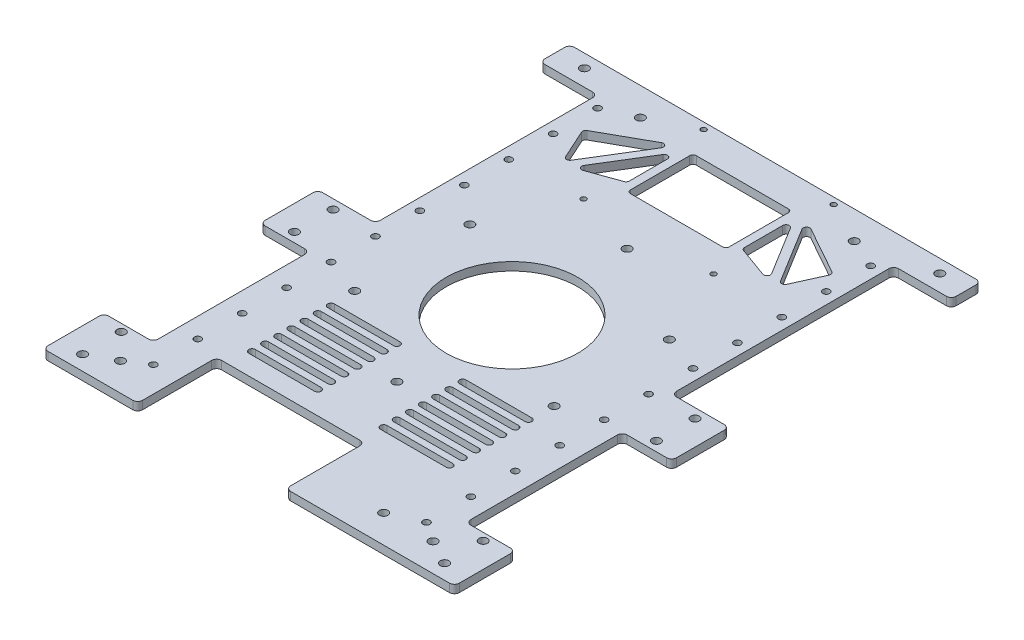
SolidWorks part; units mm, degrees
material "Thornel Mat VMA"
ref_plane "前视基准面" through (0, 0, 0) normal (0, 0, 1) x (1, 0, 0)
ref_plane "上视基准面" through (0, 0, 0) normal (0, 1, 0) x (1, 0, 0)
ref_plane "右视基准面" through (0, 0, 0) normal (1, 0, 0) x (0, 0, -1)
other "Configuration Table"
sketch "草图1" plane through (0, 0, 0) normal (0, 1, 0) x (1, 0, 0)
  line L1 (125, -160) -> (-125, -160)
  line L2 (125, -160) -> (125, 160)
  line L3 (125, 160) -> (-125, 160)
  line L4 (-125, -160) -> (-125, 160)
  line L5 (125, -160) -> (-125, 160) construction
  line L6 (125, 160) -> (-125, -160) construction
  point P0 (0, 0)
  dimension "D1" = 250
  dimension "D2" = 320
extrude "凸台-拉伸1" add sketch "草图1" along normal blind 5
sketch "草图2" plane through (0, 5, 0) normal (0, 1, 0) x (1, 0, 0)
  circle A0 centre (0, 0) radius 70 construction
  circle A1 centre (0, 70) radius 2.6
  circle A2 centre (60.6218, 35) radius 2.6
  circle A3 centre (60.6218, -35) radius 2.6
  circle A4 centre (0, -70) radius 2.6
  circle A5 centre (-60.6218, -35) radius 2.6
  circle A6 centre (-60.6218, 35) radius 2.6
  circle A7 centre (0, 0) radius 40
  point P17 (0, 0)
  dimension "D1" = 140
  dimension "D2" = 5.2
  dimension "D4" = 80
  dimension "D3" = 6
extrude "切除-拉伸1" cut sketch "草图2" against normal blind 50
sketch "草图3" plane through (0, 5, 0) normal (0, 1, 0) x (1, 0, 0)
  line L0 (-125, 160) -> (-125, -160) construction
  line L1 (-125, 142) -> (-90, 142)
  line L2 (-125, 142) -> (-125, 7)
  line L3 (-125, 7) -> (-90, 7)
  line L4 (-90, 142) -> (-90, 7)
  line L5 (-125, 0) -> (125, 0) construction
  line L6 (125, -160) -> (125, 160) construction
  line L7 (0, 160) -> (0, -160) construction
  line L8 (125, 160) -> (-125, 160) construction
  line L9 (-125, -160) -> (125, -160) construction
  line L10 (125, 7) -> (90, 7)
  line L11 (90, 142) -> (90, 7)
  line L12 (125, 142) -> (90, 142)
  line L13 (125, 142) -> (125, 7)
  line L14 (125, -123) -> (95, -123)
  line L15 (-125, -28) -> (-95, -28)
  line L16 (-125, -28) -> (-125, -123)
  line L17 (-125, -123) -> (-95, -123)
  line L18 (-95, -28) -> (-95, -123)
  line L19 (95, -28) -> (95, -123)
  line L20 (125, -28) -> (95, -28)
  line L21 (125, -28) -> (125, -123)
  dimension "D1" = 18
  dimension "D2" = 35
  dimension "D3" = 135
  dimension "D4" = 37
  dimension "D5" = 95
  dimension "D6" = 30
extrude "切除-拉伸2" cut sketch "草图3" against normal blind 50
fillet "圆角1" radius 3 20 edges at (90, 2.5, -142) (125, 2.5, -142) (125, 2.5, -160) (-125, 2.5, -160) (-90, 2.5, -142) (-90, 2.5, -7) (-125, 2.5, -7) (-125, 2.5, 28) (-95, 2.5, 28) (-95, 2.5, 123) (-125, 2.5, 123) (-125, 2.5, 160) (125, 2.5, 160) (125, 2.5, 123) (95, 2.5, 123) (95, 2.5, 28) (125, 2.5, 28) (125, 2.5, -7) (90, 2.5, -7) (-125, 2.5, -142)
sketch "草图6" plane through (0, 5, 0) normal (0, 1, 0) x (1, 0, 0)
  line L0 (-125, -10.5) -> (125, -10.5) construction
  line L1 (-125, 4) -> (-125, -25) construction
  line L2 (125, -25) -> (125, 4) construction
  line L3 (-110, 1.25) -> (-110, -22.25) construction
  line L4 (0, 160) -> (0, -160) construction
  line L5 (122, 160) -> (-122, 160) construction
  line L6 (-122, -160) -> (122, -160) construction
  line L7 (110, 1.25) -> (110, -22.25) construction
  line L8 (-110, -127.5) -> (-110, -151) construction
  line L9 (110, -127.5) -> (110, -151) construction
  circle A0 centre (-110, 1.25) radius 2.6
  circle A1 centre (-110, -22.25) radius 2.6
  circle A2 centre (110, -22.25) radius 2.6
  circle A3 centre (110, 1.25) radius 2.6
  circle A4 centre (-110, -127.5) radius 2.6
  circle A5 centre (-110, -151) radius 2.6
  circle A6 centre (110, -151) radius 2.6
  circle A7 centre (110, -127.5) radius 2.6
  dimension "D1" = 23.5
  dimension "D2" = 11.75
  dimension "D3" = 5.2
  dimension "D4" = 5.2
  dimension "D6" = 5.2
  dimension "D7" = 23.5
  dimension "D8" = 9
  dimension "D5" = 15
extrude "切除-拉伸4" cut sketch "草图6" against normal blind 100
sketch "草图7" plane through (0, 5, 0) normal (0, 1, 0) x (1, 0, 0)
  line L0 (0, 160) -> (0, -160) construction
  line L1 (122, 160) -> (-122, 160) construction
  line L2 (-122, -160) -> (122, -160) construction
  line L3 (-83, 160) -> (-83, -160) construction
  line L4 (83, 160) -> (83, -160) construction
  circle A0 centre (-83, 135) radius 2.1
  circle A1 centre (-83, 108) radius 2.1
  circle A2 centre (-83, 81) radius 2.1
  circle A3 centre (-83, 54) radius 2.1
  circle A4 centre (-83, 27) radius 2.1
  circle A5 centre (-83, 0) radius 2.1
  circle A6 centre (-83, -27) radius 2.1
  circle A7 centre (-83, -54) radius 2.1
  circle A8 centre (-83, -81) radius 2.1
  circle A9 centre (-83, -108) radius 2.1
  circle A10 centre (-83, -135) radius 2.1
  circle A11 centre (83, -135) radius 2.1
  circle A12 centre (83, -108) radius 2.1
  circle A13 centre (83, -81) radius 2.1
  circle A14 centre (83, -54) radius 2.1
  circle A15 centre (83, -27) radius 2.1
  circle A16 centre (83, 0) radius 2.1
  circle A17 centre (83, 27) radius 2.1
  circle A18 centre (83, 54) radius 2.1
  circle A19 centre (83, 81) radius 2.1
  circle A20 centre (83, 108) radius 2.1
  circle A21 centre (83, 135) radius 2.1
  dimension "D2" = 4.2
  dimension "D3" = 27
  dimension "D5" = 25
  dimension "D1" = 83
  dimension "D4" = 11
extrude "切除-拉伸5" cut sketch "草图7" against normal blind 500
sketch "草图8" plane through (0, 0, 0) normal (0, -1, 0) x (-1, 0, 0)
  line L0 (122, -160) -> (-122, -160) construction
  line L1 (-22.5, -160) -> (67.5, -160)
  line L2 (-22.5, -160) -> (-22.5, -112)
  line L3 (-22.5, -112) -> (67.5, -112)
  line L4 (67.5, -160) -> (67.5, -112)
  line L6 (125, -126) -> (125, -157) construction
  dimension "D1" = 48
  dimension "D2" = 90
  dimension "D3" = 57.5
extrude "切除-拉伸6" cut sketch "草图8" against normal blind 10
fillet "圆角2" radius 3 4 edges at (22.5, 2.5, 112) (-67.5, 2.5, 112) (22.5, 2.5, 160) (-67.5, 2.5, 160)
sketch "草图9" plane through (0, 5, 0) normal (0, 1, 0) x (1, 0, 0)
  line L0 (0, 160) -> (0, 0) construction
  line L1 (122, 160) -> (-122, 160) construction
  line L3 (39.5, 156) -> (-39.5, 156) construction
  line L4 (39.5, 156) -> (39.5, 83) construction
  line L5 (39.5, 83) -> (-39.5, 83) construction
  line L6 (-39.5, 156) -> (-39.5, 83) construction
  line L7 (39.5, 156) -> (-39.5, 83) construction
  line L8 (39.5, 83) -> (-39.5, 156) construction
  circle A0 centre (-39.5, 156) radius 1.6
  circle A1 centre (39.5, 156) radius 1.6
  circle A2 centre (39.5, 83) radius 1.6
  circle A3 centre (-39.5, 83) radius 1.6
  point P5 (0, 119.5)
  dimension "D4" = 3.2
  dimension "D1" = 79
  dimension "D2" = 73
  dimension "D3" = 4
extrude "切除-拉伸7" cut sketch "草图9" against normal blind 10
sketch "草图10" plane through (0, 5, 0) normal (0, 1, 0) x (1, 0, 0)
  line L0 (-125, 152) -> (125, 152) construction
  line L1 (-125, 157) -> (-125, 145) construction
  line L2 (125, 145) -> (125, 157) construction
  line L3 (-93, 142) -> (-122, 142) construction
  line L4 (-125, -126) -> (-125, -157) construction
  line L5 (-122, -160) -> (-70.5, -160) construction
  line L6 (0, 0) -> (0, -216.7517) construction
  circle A0 centre (-108, 152) radius 2.6
  circle A1 centre (108, 152) radius 2.6
  circle A2 centre (-95, -143) radius 2.6
  circle A3 centre (95, -143) radius 2.6
  dimension "D1" = 5.2
  dimension "D2" = 17
  dimension "D3" = 5.2
  dimension "D4" = 17
  dimension "D6" = 5.2
  dimension "D7" = 30
  dimension "D8" = 17
  dimension "D5" = 10
extrude "切除-拉伸8" cut sketch "草图10" against normal blind 10
sketch "草图12" plane through (0, 5, 0) normal (0, 1, 0) x (1, 0, 0)
  line L0 (65, 160) -> (65, -160) construction
  line L1 (122, 160) -> (-122, 160) construction
  line L2 (25.5, -160) -> (122, -160) construction
  line L3 (125, -25) -> (125, 4) construction
  line L4 (0, 160) -> (0, -112) construction
  line L5 (19.5, -112) -> (-64.5, -112) construction
  circle A0 centre (65, 143) radius 2.6
  circle A2 centre (65, -143) radius 2.6
  circle A3 centre (-65, 143) radius 2.6
  dimension "D2" = 5.2
  dimension "D3" = 17
  dimension "D4" = 17
  dimension "D1" = 60
extrude "切除-拉伸9" cut sketch "草图12" against normal blind 10
sketch "草图13" plane through (0, 5, 0) normal (0, 1, 0) x (1, 0, 0)
  line L4 (0, 160) -> (0, -112) construction
  line L5 (-30, 140) -> (30, 140)
  line L6 (-30, 140) -> (-30, 100)
  line L7 (-30, 100) -> (30, 100)
  line L8 (30, 140) -> (30, 100)
  line L9 (122, 160) -> (-122, 160) construction
  line L10 (19.5, -112) -> (-64.5, -112) construction
  line L11 (35, 136.5726) -> (35, 104.9002)
  line L12 (35, 104.9002) -> (60, 95.925)
  line L13 (60, 95.925) -> (35, 136.5726)
  line L14 (38.762, 140) -> (65.6284, 96.3179)
  line L15 (65.6284, 96.3179) -> (76, 119.1776)
  line L16 (76, 119.1776) -> (38.762, 140)
  line L17 (-65.6284, 96.3179) -> (-76, 119.1776)
  line L18 (-38.762, 140) -> (-65.6284, 96.3179)
  line L19 (-76, 119.1776) -> (-38.762, 140)
  line L20 (-35, 104.9002) -> (-60, 95.925)
  line L21 (-35, 136.5726) -> (-35, 104.9002)
  line L22 (-60, 95.925) -> (-35, 136.5726)
  line L23 (-90, 10) -> (-90, 139) construction
  line L24 (-60, -50) -> (-20, -50) construction
  line L25 (-60, -48) -> (-20, -48)
  line L26 (-60, -52) -> (-20, -52)
  line L27 (-98, -28) -> (-122, -28) construction
  line L28 (-60, -58) -> (-20, -58) construction
  line L29 (-60, -56) -> (-20, -56)
  line L30 (-60, -60) -> (-20, -60)
  line L31 (-60, -66) -> (-20, -66) construction
  line L32 (-60, -64) -> (-20, -64)
  line L33 (-60, -68) -> (-20, -68)
  line L34 (-60, -74) -> (-20, -74) construction
  line L35 (-60, -72) -> (-20, -72)
  line L36 (-60, -76) -> (-20, -76)
  line L37 (-60, -82) -> (-20, -82) construction
  line L38 (-60, -80) -> (-20, -80)
  line L39 (-60, -84) -> (-20, -84)
  line L40 (-60, -90) -> (-20, -90) construction
  line L41 (-60, -88) -> (-20, -88)
  line L42 (-60, -92) -> (-20, -92)
  line L43 (60, -90) -> (20, -90) construction
  line L44 (60, -88) -> (20, -88)
  line L45 (60, -92) -> (20, -92)
  line L46 (60, -82) -> (20, -82) construction
  line L47 (60, -80) -> (20, -80)
  line L48 (60, -84) -> (20, -84)
  line L49 (60, -74) -> (20, -74) construction
  line L50 (60, -72) -> (20, -72)
  line L51 (60, -76) -> (20, -76)
  line L52 (60, -66) -> (20, -66) construction
  line L53 (60, -64) -> (20, -64)
  line L54 (60, -68) -> (20, -68)
  line L55 (60, -58) -> (20, -58) construction
  line L56 (60, -56) -> (20, -56)
  line L57 (60, -60) -> (20, -60)
  line L58 (60, -50) -> (20, -50) construction
  line L59 (60, -48) -> (20, -48)
  line L60 (60, -52) -> (20, -52)
  line L61 (-60, -98) -> (-20, -98) construction
  line L62 (-60, -96) -> (-20, -96)
  line L63 (-60, -100) -> (-20, -100)
  line L64 (60, -98) -> (20, -98) construction
  line L67 (60, -96) -> (20, -96)
  line L68 (60, -100) -> (20, -100)
  arc A0 (-60, -48) -> (-60, -52) centre (-60, -50) ccw
  arc A1 (-20, -52) -> (-20, -48) centre (-20, -50) ccw
  arc A2 (-60, -56) -> (-60, -60) centre (-60, -58) ccw
  arc A3 (-20, -60) -> (-20, -56) centre (-20, -58) ccw
  arc A4 (-60, -64) -> (-60, -68) centre (-60, -66) ccw
  arc A5 (-20, -68) -> (-20, -64) centre (-20, -66) ccw
  arc A6 (-60, -72) -> (-60, -76) centre (-60, -74) ccw
  arc A7 (-20, -76) -> (-20, -72) centre (-20, -74) ccw
  arc A8 (-60, -80) -> (-60, -84) centre (-60, -82) ccw
  arc A9 (-20, -84) -> (-20, -80) centre (-20, -82) ccw
  arc A10 (-60, -88) -> (-60, -92) centre (-60, -90) ccw
  arc A11 (-20, -92) -> (-20, -88) centre (-20, -90) ccw
  arc A12 (60, -88) -> (60, -92) centre (60, -90) cw
  arc A13 (20, -92) -> (20, -88) centre (20, -90) cw
  arc A14 (60, -80) -> (60, -84) centre (60, -82) cw
  arc A15 (20, -84) -> (20, -80) centre (20, -82) cw
  arc A16 (60, -72) -> (60, -76) centre (60, -74) cw
  arc A17 (20, -76) -> (20, -72) centre (20, -74) cw
  arc A18 (60, -64) -> (60, -68) centre (60, -66) cw
  arc A19 (20, -68) -> (20, -64) centre (20, -66) cw
  arc A20 (60, -56) -> (60, -60) centre (60, -58) cw
  arc A21 (20, -60) -> (20, -56) centre (20, -58) cw
  arc A22 (60, -48) -> (60, -52) centre (60, -50) cw
  arc A23 (20, -52) -> (20, -48) centre (20, -50) cw
  arc A24 (-60, -96) -> (-60, -100) centre (-60, -98) ccw
  arc A25 (-20, -100) -> (-20, -96) centre (-20, -98) ccw
  arc A28 (60, -96) -> (60, -100) centre (60, -98) cw
  arc A29 (20, -100) -> (20, -96) centre (20, -98) cw
  point P27 (-40, -50)
  point P38 (-40, -58)
  point P45 (-40, -66)
  point P52 (-40, -74)
  point P59 (-40, -82)
  point P66 (-40, -90)
  point P71 (40, -90)
  point P78 (40, -82)
  point P85 (40, -74)
  point P92 (40, -66)
  point P99 (40, -58)
  point P106 (40, -50)
  point P114 (-40, -98)
  point P121 (40, -98)
  dimension "D10" = 2
  dimension "D12" = 20
  dimension "D1" = 60
  dimension "D2" = 30
  dimension "D3" = 20
  dimension "D4" = 40
  dimension "D5" = 5
  dimension "D6" = 5
  dimension "D7" = 14
  dimension "D8" = 20
  dimension "D9" = 30
  dimension "D11" = 40
  dimension "D13" = 20
  dimension "D15" = 4
  dimension "D14" = 7
extrude "切除-拉伸10" cut sketch "草图13" against normal blind 10
fillet "圆角3" radius 2 16 edges at (30, 2.5, -140) (30, 2.5, -100) (-30, 2.5, -100) (-30, 2.5, -140) (-76, 2.5, -119.1776) (-65.6284, 2.5, -96.3179) (-60, 2.5, -95.925) (-35, 2.5, -136.5726) (-35, 2.5, -104.9002) (35, 2.5, -104.9002) (35, 2.5, -136.5726) (60, 2.5, -95.925) (65.6284, 2.5, -96.3179) (38.762, 2.5, -140) (76, 2.5, -119.1776) (-38.762, 2.5, -140)
